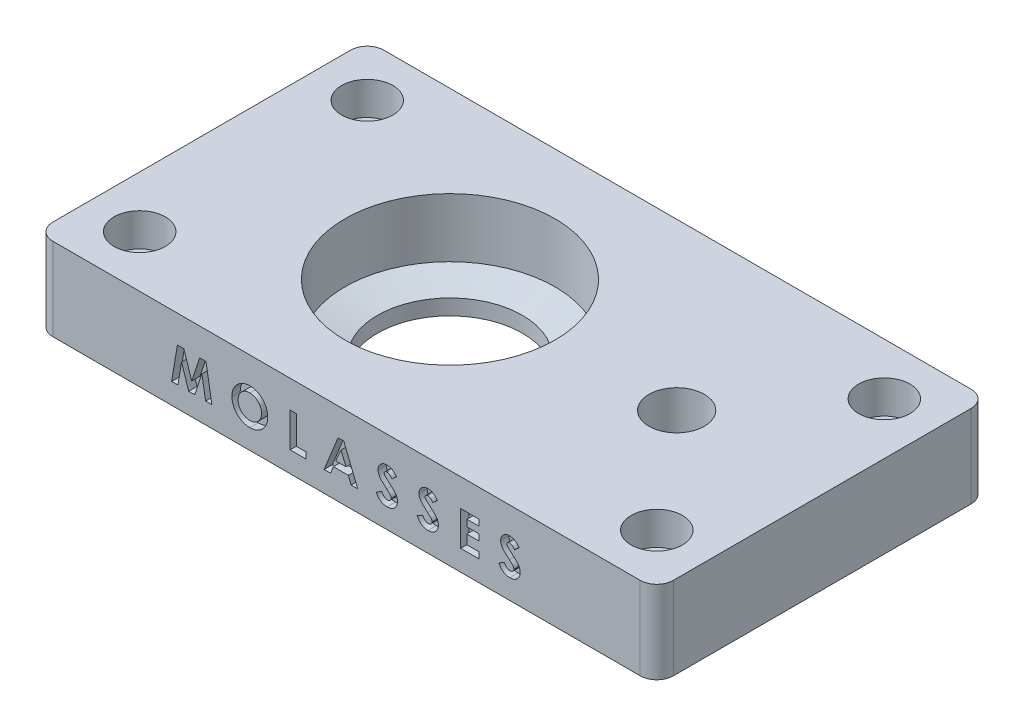
SolidWorks part; units mm, degrees
material "ABS"
ref_plane "Front Plane" through (0, 0, 0) normal (0, 0, 1) x (1, 0, 0)
ref_plane "Top Plane" through (0, 0, 0) normal (0, 1, 0) x (1, 0, 0)
ref_plane "Right Plane" through (0, 0, 0) normal (1, 0, 0) x (0, 0, -1)
sketch "Sketch1" plane through (0, 0, 0) normal (0, 1, 0) x (1, 0, 0)
  line L0 (0, 0) -> (34.798, 0) construction
  line L1 (-38.1, -25.4) -> (57.15, -25.4)
  line L2 (-38.1, -25.4) -> (-38.1, 25.4)
  line L3 (-38.1, 25.4) -> (57.15, 25.4)
  line L4 (57.15, -25.4) -> (57.15, 25.4)
  point P0 (0, 0)
  dimension "D1" = 95.25
  dimension "D2" = 50.8
  dimension "D3" = 34.798
extrude "Boss-Extrude1" add sketch "Sketch1" along normal blind 12.7
sketch "Sketch4" plane through (0, 12.7, 0) normal (0, 1, 0) x (1, 0, 0)
  line L5 (57.15, -25.4) -> (57.15, 25.4) construction
  line L6 (-38.1, -25.4) -> (57.15, -25.4) construction
  line L7 (57.15, 25.4) -> (-38.1, 25.4) construction
  line L8 (-38.1, 25.4) -> (-38.1, -25.4) construction
  circle A0 centre (-30.1625, 17.4625) radius 2.54
  circle A1 centre (49.2125, 17.4625) radius 2.54
  circle A2 centre (49.2125, -17.4625) radius 2.54
  circle A3 centre (-30.1625, -17.4625) radius 2.54
  point P0 (0, 0)
  dimension "D3" = 5.08
  dimension "D4" = 5.08
  dimension "D5" = 5.08
  dimension "D6" = 5.08
  dimension "D1" = 7.9375
  dimension "D2" = 7.9375
  dimension "D9" = 7.9375
  dimension "D7" = 7.9375
  dimension "D8" = 7.9375
  dimension "D10" = 7.9375
  dimension "D11" = 7.9375
  dimension "D12" = 7.9375
extrude "Cut-Extrude3" cut sketch "Sketch4" against normal through all
fillet "Fillet2" radius 2.54 4 edges at (-38.1, 6.35, 25.4) (57.15, 6.35, 25.4) (57.15, 6.35, -25.4) (-38.1, 6.35, -25.4)
sketch "Sketch6" plane through (0, 0, 0) normal (0, 0, 1) x (1, 0, 0)
  line L0 (0, 0) -> (0, 12.7)
  line L1 (-35.56, 12.7) -> (54.61, 12.7) construction
  line L2 (0, 12.7) -> (-16.129, 12.7)
  line L3 (-16.129, 12.7) -> (-16.129, 3.6513)
  line L5 (-35.56, 0) -> (54.61, 0) construction
  line L6 (-11.1125, 0) -> (0, 0)
  line L7 (-11.1125, 0) -> (-11.1125, 2.3813)
  line L8 (-11.1125, 2.3813) -> (-16.129, 3.6513)
  line L9 (-38.1, 0) -> (-38.1, 12.7) construction
  dimension "D1" = 16.129
  dimension "D2" = 11.1125
  dimension "D3" = 1.27
  dimension "D4" = 2.3813
  dimension "D5" = 38.1
revolve "Cut-Revolve1" cut sketch "Sketch6" angle 360 about L0
sketch "Sketch8" plane through (0, 12.7, 0) normal (0, 1, 0) x (1, 0, 0)
  line L0 (57.15, -22.86) -> (57.15, 22.86) construction
  circle A1 centre (34.798, 0) radius 4.25
  circle A2 centre (0, 0) radius 11.1125 construction
  point P5 (57.15, 0)
  dimension "D1" = 34.798
  dimension "D2" = 8.5
extrude "Cut-Extrude4" cut sketch "Sketch8" against normal blind 6.35
sketch "Sketch9" plane through (0, 0, 25.4) normal (0, 0, 1) x (1, 0, 0)
  line L0 (-35.56, 3.175) -> (54.61, 3.175) construction
  line L1 (-35.56, 12.7) -> (-35.56, 0) construction
  line L2 (54.61, 0) -> (54.61, 12.7) construction
  text T0 "<b>MOLASSES</b>" font "Century Gothic" height in points 20
  point P6 (-35.56, 6.35)
  dimension "D1" = 3.175
extrude "Cut-Extrude5" cut sketch "Sketch9" against normal blind 1.27
sketch "Sketch10" plane through (0, 12.7, 0) normal (0, 1, 0) x (1, 0, 0)
  circle A0 centre (-30.1625, 17.4625) radius 3.937
  circle A1 centre (-30.1625, -17.4625) radius 3.937
  circle A2 centre (49.2125, 17.4625) radius 3.937
  circle A3 centre (49.2125, -17.4625) radius 3.937
  dimension "D1" = 7.874
  dimension "D2" = 7.874
  dimension "D3" = 7.874
  dimension "D4" = 7.874
extrude "Cut-Extrude6" cut sketch "Sketch10" against normal blind 5.08
